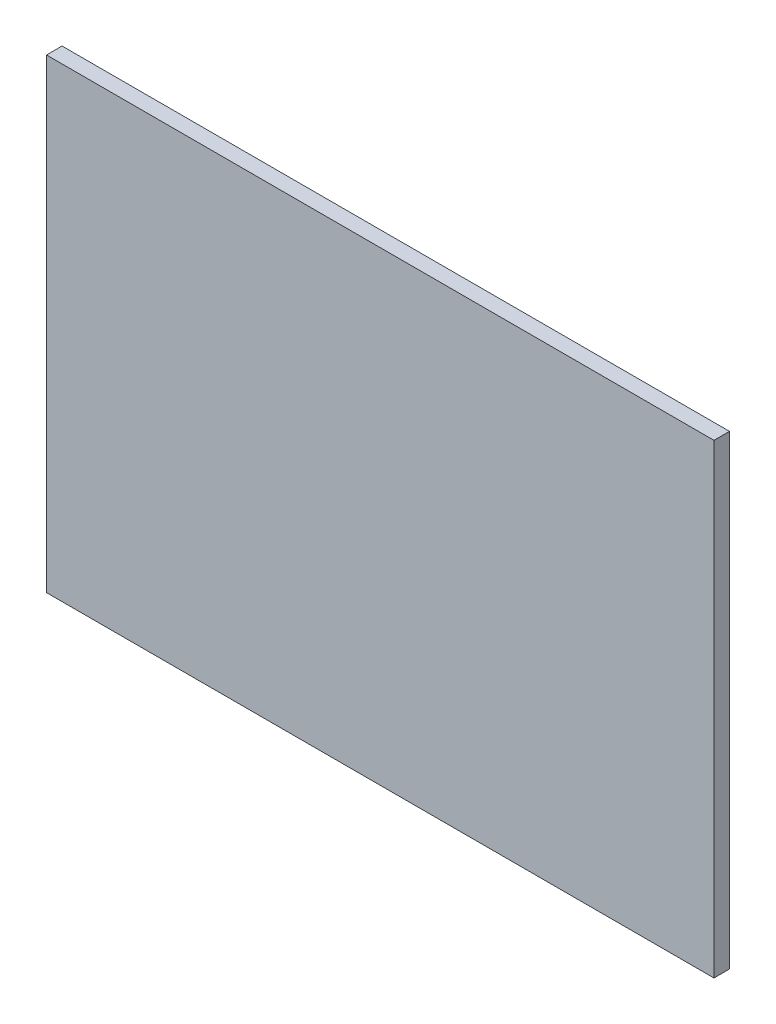
SolidWorks part; units mm, degrees
ref_plane "Front Plane" through (0, 0, 0) normal (0, 0, 1) x (1, 0, 0)
ref_plane "Top Plane" through (0, 0, 0) normal (0, 1, 0) x (1, 0, 0)
ref_plane "Right Plane" through (0, 0, 0) normal (1, 0, 0) x (0, 0, -1)
sketch "Sketch1" plane through (0, 0, 0) normal (0, 0, 1) x (1, 0, 0)
  line L0 (-162.561, 300) -> (267.439, 300)
  line L1 (267.439, 300) -> (267.439, 0)
  line L2 (267.439, 0) -> (-162.561, 0)
  line L3 (-162.561, 0) -> (-162.561, 300)
  dimension "D1" = 430
  dimension "D2" = 300
extrude "Boss-Extrude1" add sketch "Sketch1" along normal blind 10
